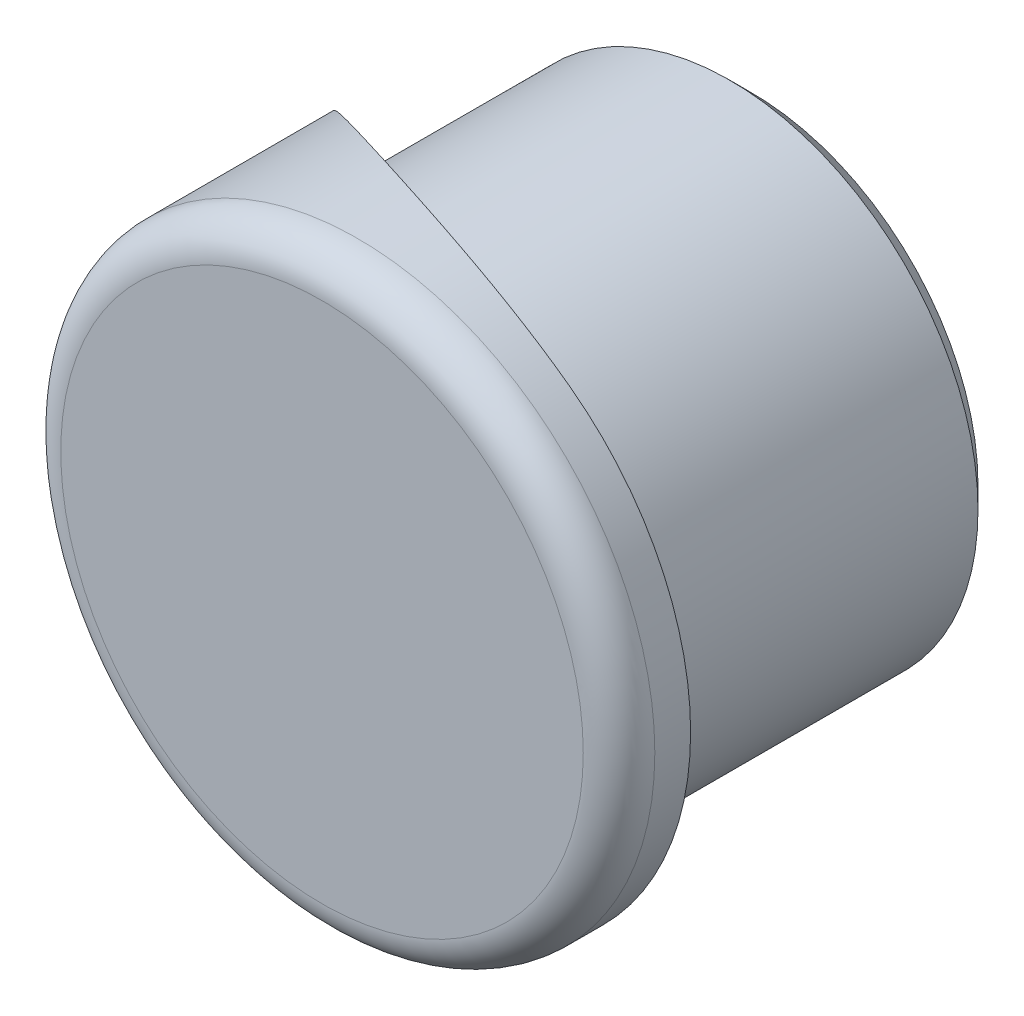
SolidWorks part; units mm, degrees
ref_plane "Plan de face" through (0, 0, 0) normal (0, 0, 1) x (1, 0, 0)
ref_plane "Plan de dessus" through (0, 0, 0) normal (0, 1, 0) x (1, 0, 0)
ref_plane "Plan de droite" through (0, 0, 0) normal (1, 0, 0) x (0, 0, -1)
sketch "Esquisse1" plane through (0, 0, 0) normal (0, 0, 1) x (1, 0, 0)
  circle A0 centre (-38, 67) radius 3.465
  dimension "D1" = 6.93
extrude "Boss.-Extru.1" add sketch "Esquisse1" against normal blind 5
sketch "Esquisse2" plane through (0, 0, 0) normal (0, 0, 1) x (1, 0, 0)
  circle A0 centre (-38, 67) radius 4.15
  dimension "D1" = 8.3
extrude "Boss.-Extru.2" add sketch "Esquisse2" along normal blind 1
fillet "Congé1" radius 0.5 1 edges at (-33.85, 67, 1)
ref_plane "Plan1" through (-41.465, 0, 0) normal (-1, 0, 0) x (0, 0, 1)
ref_plane "Plan2" through (0, 71.15, 0) normal (0, 1, 0) x (1, 0, 0)
sketch "Esquisse4" plane through (29.785, 71.15, 0) normal (0, -1, 0) x (0, 0, 1)
  line L0 (-5, 67.785) -> (1, 67.785) construction
  line L1 (-5, 71.25) -> (-5, 64.32) construction
  line L2 (1, 64.135) -> (1, 71.435) construction
  line L3 (-5, 65.32) -> (0, 65.32) construction
  line L4 (0, 71.25) -> (0, 64.32) construction
  line L5 (0, 71.935) -> (-3.5009, 71.935)
  line L6 (0, 71.935) -> (0, 65.32)
  line L8 (-5, 64.32) -> (0, 64.32) construction
  arc A0 (0, 65.32) -> (-3.5009, 71.935) centre (-8, 65.32) ccw
  dimension "D2" = 8
  dimension "D1" = 1
extrude "Boss.-Extru.3" add sketch "Esquisse4" along normal blind 9 and the other way blind 2
sketch "Esquisse5" plane through (0, 0, 1) normal (0, 0, 1) x (1, 0, 0)
  line L0 (-35.535, 63.6614) -> (-34.4842, 58.9113)
  line L1 (-34.4842, 58.9113) -> (-43.8082, 59.4661)
  line L2 (-43.8082, 59.4661) -> (-42.997, 73.4865)
  line L3 (-42.997, 73.4865) -> (-34.8167, 73.4865)
  line L4 (-34.8167, 73.4865) -> (-35.535, 70.3386)
  arc A0 (-42.15, 67) -> (-35.535, 63.6614) centre (-38, 67) ccw construction
  arc A1 (-42.15, 67) -> (-35.535, 63.6614) centre (-38, 67) ccw
  arc A2 (-35.535, 70.3386) -> (-42.15, 67) centre (-38, 67) ccw construction
  arc A3 (-35.535, 70.3386) -> (-42.15, 67) centre (-38, 67) ccw
extrude "Enlèv. mat.-Extru.1" cut sketch "Esquisse5" against normal blind 8
chamfer "Chanfrein1" distance 0.3 angle 45 1 edges at (-34.535, 67, -5)
sketch "Esquisse7" plane through (0, 0, -5) normal (0, 0, -1) x (-1, 0, 0)
  line L0 (39.1602, 63.735) -> (36.8398, 63.735)
  arc A2 (35.535, 64.5648) -> (35.535, 69.4352) centre (38, 67) ccw construction
  arc A3 (36.8398, 63.735) -> (39.1602, 63.735) centre (38, 67) ccw
  point P3 (36.1658, 64.0603)
  point P4 (38, 63.535)
  point P5 (39.8182, 64.0504)
  point P8 (0, 0)
  point P9 (38, 63.535)
  dimension "D1" = 0.2
extrude "Enlèv. mat.-Extru.2" cut sketch "Esquisse7" against normal up to surface (4.1315 mm away)
